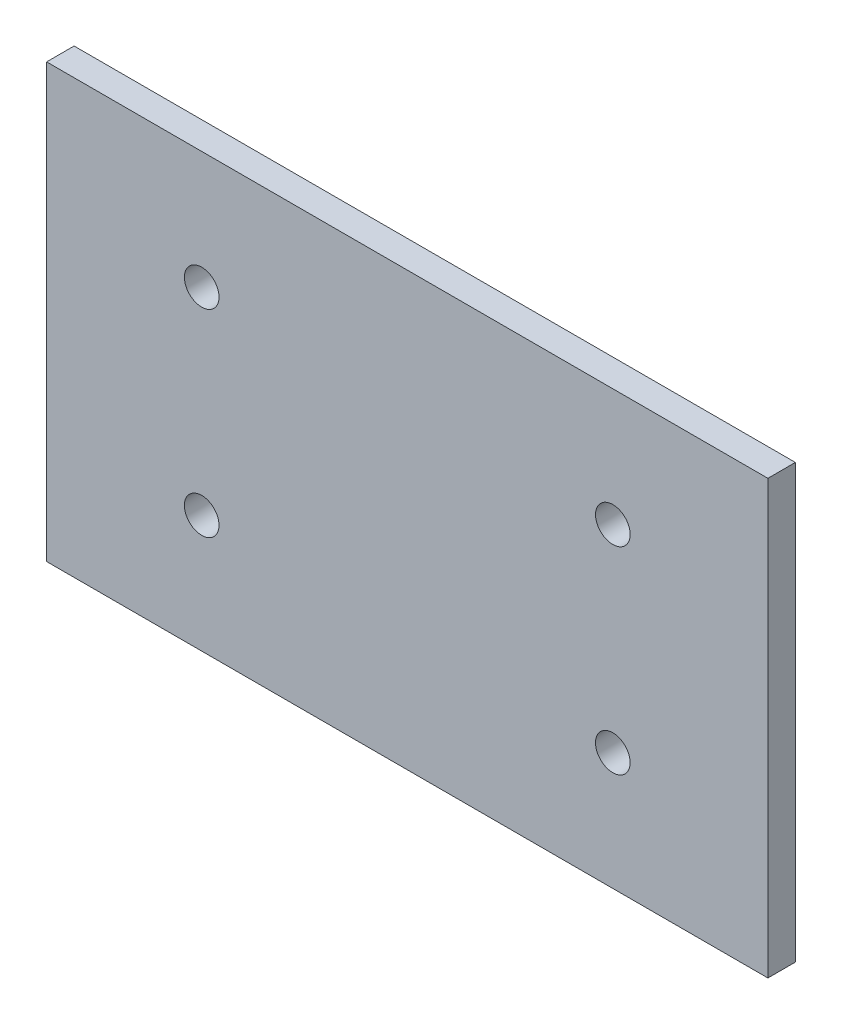
SolidWorks part; units mm, degrees
ref_plane "Front Plane" through (0, 0, 0) normal (0, 0, 1) x (1, 0, 0)
ref_plane "Top Plane" through (0, 0, 0) normal (0, 1, 0) x (1, 0, 0)
ref_plane "Right Plane" through (0, 0, 0) normal (1, 0, 0) x (0, 0, -1)
sketch "Sketch1" plane through (0, 0, 0) normal (0, 0, 1) x (1, 0, 0)
  line L1 (0, 0) -> (250, 0)
  line L2 (0, 0) -> (0, -150)
  line L3 (0, -150) -> (250, -150)
  line L4 (250, 0) -> (250, -150)
  circle A0 centre (53.75, -40.75) radius 6
  circle A1 centre (196.25, -40.75) radius 6
  circle A2 centre (196.25, -109.25) radius 6
  circle A3 centre (53.75, -109.25) radius 6
  dimension "D3" = 12
  dimension "D4" = 12
  dimension "D5" = 12
  dimension "D6" = 12
  dimension "D7" = 40.75
  dimension "D8" = 40.75
  dimension "D9" = 53.75
  dimension "D10" = 53.75
  dimension "D1" = 250
  dimension "D2" = 150
extrude "Boss-Extrude1" add sketch "Sketch1" along normal blind 9.525 contours L1 L4 L3 L2
